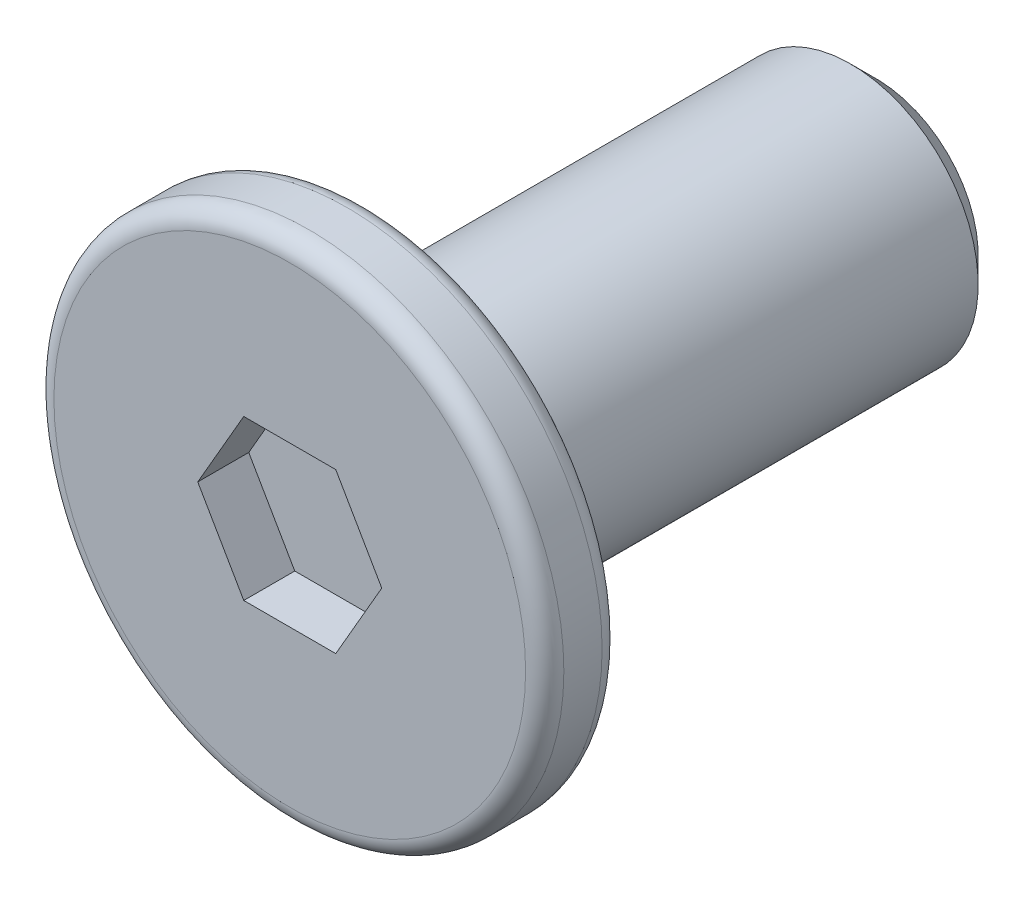
SolidWorks part; units mm, degrees
ref_plane "前视基准面" through (0, 0, 0) normal (0, 0, 1) x (1, 0, 0)
ref_plane "上视基准面" through (0, 0, 0) normal (0, 1, 0) x (1, 0, 0)
ref_plane "右视基准面" through (0, 0, 0) normal (1, 0, 0) x (0, 0, -1)
sketch "草图1" plane through (0, 0, 0) normal (0, 0, 1) x (1, 0, 0)
  circle A0 centre (0, 0) radius 4
  dimension "D1" = 8
extrude "凸台-拉伸1" add sketch "草图1" along normal mid plane 1.2
sketch "草图2" plane through (0, 0, -0.6) normal (0, 0, -1) x (-1, 0, 0)
  circle A0 centre (0, 0) radius 2
  dimension "D1" = 4
extrude "凸台-拉伸2" add sketch "草图2" along normal blind 8
chamfer "倒角1" distance 0.4 angle 45 1 edges at (-2, 0, -8.6)
sketch "草图3" plane through (0, 0, 0.6) normal (0, 0, 1) x (1, 0, 0)
  line L1 (1.4434, 0) -> (0.7217, 1.25)
  line L2 (0.7217, 1.25) -> (-0.7217, 1.25)
  line L3 (-0.7217, 1.25) -> (-1.4434, 0)
  line L4 (-1.4434, 0) -> (-0.7217, -1.25)
  line L5 (-0.7217, -1.25) -> (0.7217, -1.25)
  line L6 (0.7217, -1.25) -> (1.4434, 0)
  circle A0 centre (0, 0) radius 1.25 construction
  dimension "D1" = 2.5
extrude "切除-拉伸1" cut sketch "草图3" against normal blind 0.8
fillet "圆角2" radius 0.3 2 edges at (4, 0, -0.6) (4, 0, 0.6)
